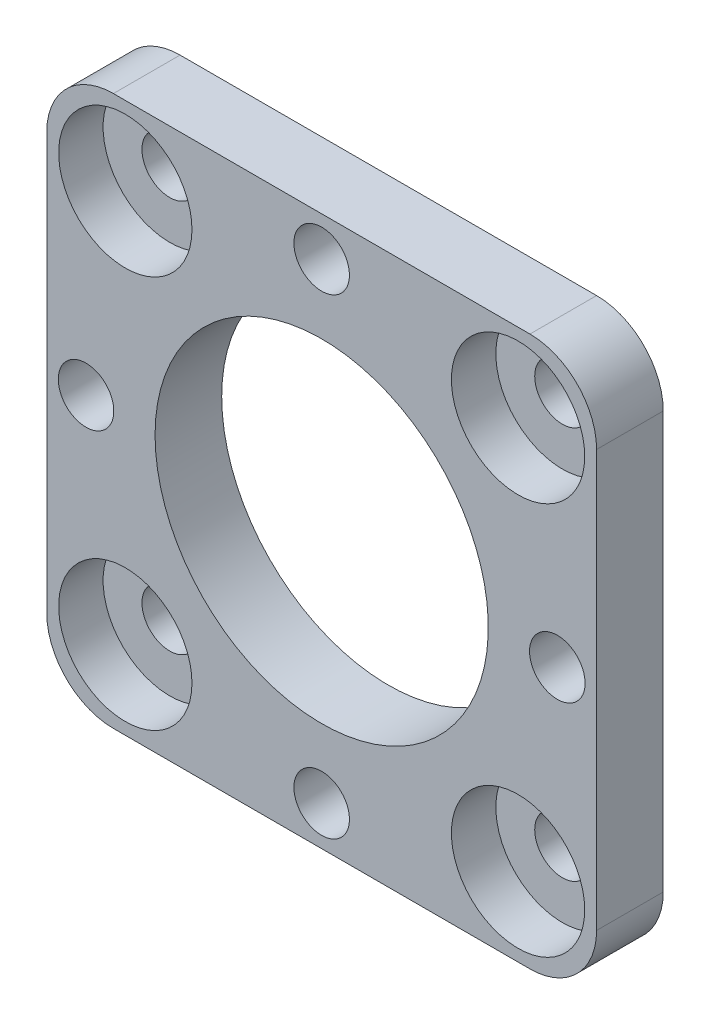
SolidWorks part; units mm, degrees
ref_plane "前视基准面" through (0, 0, 0) normal (0, 0, 1) x (1, 0, 0)
ref_plane "上视基准面" through (0, 0, 0) normal (0, 1, 0) x (1, 0, 0)
ref_plane "右视基准面" through (0, 0, 0) normal (1, 0, 0) x (0, 0, -1)
sketch "草图1" plane through (0, 0, 0) normal (0, 0, 1) x (1, 0, 0)
  circle A0 centre (0, 0) radius 17.5
  dimension "D1" = 35
extrude "凸台-拉伸1" add sketch "草图1" along normal blind 3
sketch "草图2" plane through (0, 0, 0) normal (0, 0, -1) x (-1, 0, 0)
  line L1 (-8.8388, -8.8388) -> (8.8388, -8.8388) construction
  line L2 (-8.8388, -8.8388) -> (-8.8388, 8.8388) construction
  line L3 (-8.8388, 8.8388) -> (8.8388, 8.8388) construction
  line L4 (8.8388, -8.8388) -> (8.8388, 8.8388) construction
  line L5 (-8.8388, -8.8388) -> (8.8388, 8.8388) construction
  line L6 (-8.8388, 8.8388) -> (8.8388, -8.8388) construction
  circle A0 centre (-8.8388, 8.8388) radius 1.25
  circle A1 centre (8.8388, 8.8388) radius 1.25
  circle A2 centre (8.8388, -8.8388) radius 1.25
  circle A3 centre (-8.8388, -8.8388) radius 1.25
  point P0 (0, 0)
  dimension "D2" = 2.5
  dimension "D1" = 25
extrude "切除-拉伸1" cut sketch "草图2" against normal up to next
cosmetic thread "装饰螺纹线5" parameters "D2"=3
cosmetic thread "装饰螺纹线6" parameters "D2"=3
cosmetic thread "装饰螺纹线7" parameters "D2"=3
cosmetic thread "装饰螺纹线8" parameters "D2"=3
sketch "草图3" plane through (0, 0, 0) normal (0, 0, -1) x (-1, 0, 0)
  line L0 (-10.6066, 0) -> (0, 10.6066) construction
  line L1 (-10.6066, 0) -> (0, -10.6066) construction
  line L2 (0, 10.6066) -> (10.6066, 0) construction
  line L3 (0, -10.6066) -> (10.6066, 0) construction
  line L4 (-10.6066, 0) -> (10.6066, 0) construction
  line L5 (0, 10.6066) -> (0, -10.6066) construction
  line L6 (-8.8388, 8.8388) -> (8.8388, -8.8388) construction
  circle A0 centre (0, 10.6066) radius 1.25
  circle A1 centre (-10.6066, 0) radius 1.25
  circle A2 centre (0, -10.6066) radius 1.25
  circle A3 centre (10.6066, 0) radius 1.25
  point P1 (0, 0)
  dimension "D2" = 2.5
  dimension "D1" = 15
extrude "切除-拉伸2" cut sketch "草图3" against normal up to next
cosmetic thread "装饰螺纹线1" parameters "D2"=3
cosmetic thread "装饰螺纹线2" parameters "D2"=3
cosmetic thread "装饰螺纹线3" parameters "D2"=3
cosmetic thread "装饰螺纹线4" parameters "D2"=3
sketch "草图4" plane through (0, 0, 0) normal (0, 0, -1) x (-1, 0, 0)
  circle A0 centre (0, 0) radius 7.5
  dimension "D1" = 15
extrude "切除-拉伸3" cut sketch "草图4" against normal up to next
sketch "草图6" plane through (0, 0, 3) normal (0, 0, 1) x (1, 0, 0)
  point P0 (0, 0)
sketch "草图7" plane through (0, 0, 3) normal (0, 0, 1) x (1, 0, 0)
  line L1 (12.3744, -12.3744) -> (-12.3744, -12.3744)
  line L2 (12.3744, -12.3744) -> (12.3744, 12.3744)
  line L3 (12.3744, 12.3744) -> (-12.3744, 12.3744)
  line L4 (-12.3744, -12.3744) -> (-12.3744, 12.3744)
  line L5 (12.3744, -12.3744) -> (-12.3744, 12.3744) construction
  line L6 (12.3744, 12.3744) -> (-12.3744, -12.3744) construction
  circle A0 centre (0, 0) radius 17.5 construction
  circle A1 centre (0, 0) radius 17.5
  point P0 (0, 0)
  circle M14 centre (0, 0) radius 17.5
extrude "切除-拉伸4" cut sketch "草图7" against normal up to next contours L3 M14 | L2 M14 | L1 M14 | L4 M14
fillet "圆角1" radius 3 4 edges at (12.3744, -12.3744, 1.5) (12.3744, 12.3744, 1.5) (-12.3744, -12.3744, 1.5) (-12.3744, 12.3744, 1.5)
sketch "草图8" plane through (0, 0, 3) normal (0, 0, 1) x (1, 0, 0)
  circle A0 centre (-8.8388, 8.8388) radius 3
  circle A1 centre (8.8388, 8.8388) radius 3
  circle A2 centre (8.8388, -8.8388) radius 3
  circle A3 centre (-8.8388, -8.8388) radius 3
  dimension "D1" = 6
extrude "切除-拉伸5" cut sketch "草图8" against normal blind 2
